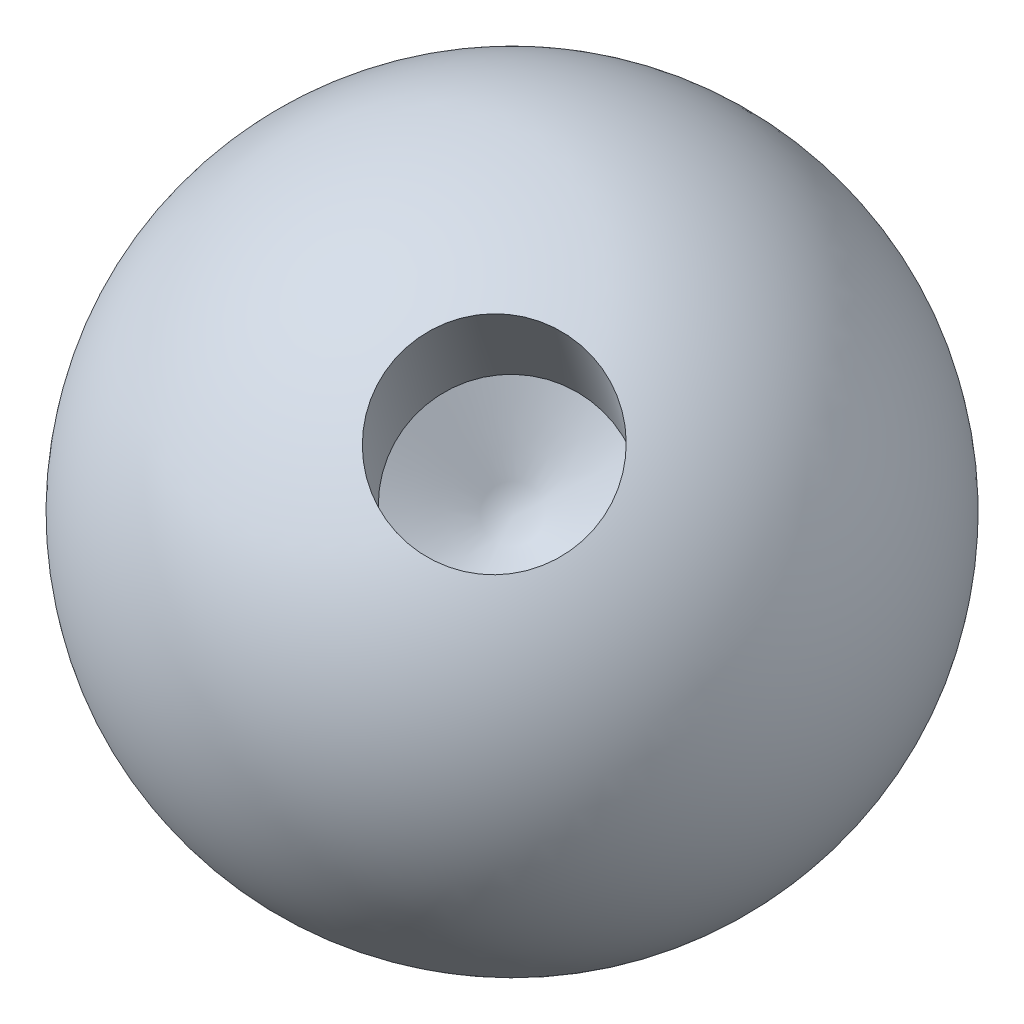
SolidWorks part; units mm, degrees
ref_plane "Front Plane" through (0, 0, 0) normal (0, 0, 1) x (1, 0, 0)
ref_plane "Top Plane" through (0, 0, 0) normal (0, 1, 0) x (1, 0, 0)
ref_plane "Right Plane" through (0, 0, 0) normal (1, 0, 0) x (0, 0, -1)
sketch "Sketch1" plane through (0, 0, 0) normal (0, 0, 1) x (1, 0, 0)
  line L0 (0, 15) -> (0, -15)
  arc A0 (0, -15) -> (0, 15) centre (0, 0) ccw
  dimension "D1" = 30
revolve "Revolve1" add sketch "Sketch1" angle 360 about L0
hole_wizard "M10x1.5 Tapped Hole1" positions "3DSketch1" profile "Sketch2" tap size "M10x1.5" standard "ANSI Metric"
sketch3d "3DSketch1"
  point P0 (0, 0, 0)
  point P3 (7.2043, 10.4069, 8.0495)
sketch "Sketch2" plane through (7.2043, 10.4069, 8.0495) normal (0.491, -0.7196, 0.491) x (-0.7268, -0.0277, 0.6863)
  line L0 (0, 0) -> (0, 16.0537)
  line L1 (0, 16.0537) -> (4.25, 13.5)
  line L2 (4.25, 13.5) -> (4.25, 0)
  line L5 (4.25, 0) -> (0, 0)
  line L10 (0, 16.0537) -> (-4.25, 13.5) construction
  line L11 (0, -6.35) -> (0, 107.95) construction
  dimension "Tap Drill Dia." = 8.5
  dimension "Tap Drill Depth" = 13.5
  dimension "Drill Angle" = 118
cosmetic thread "Hole Thread1"
cosmetic thread "Hole Thread2"
